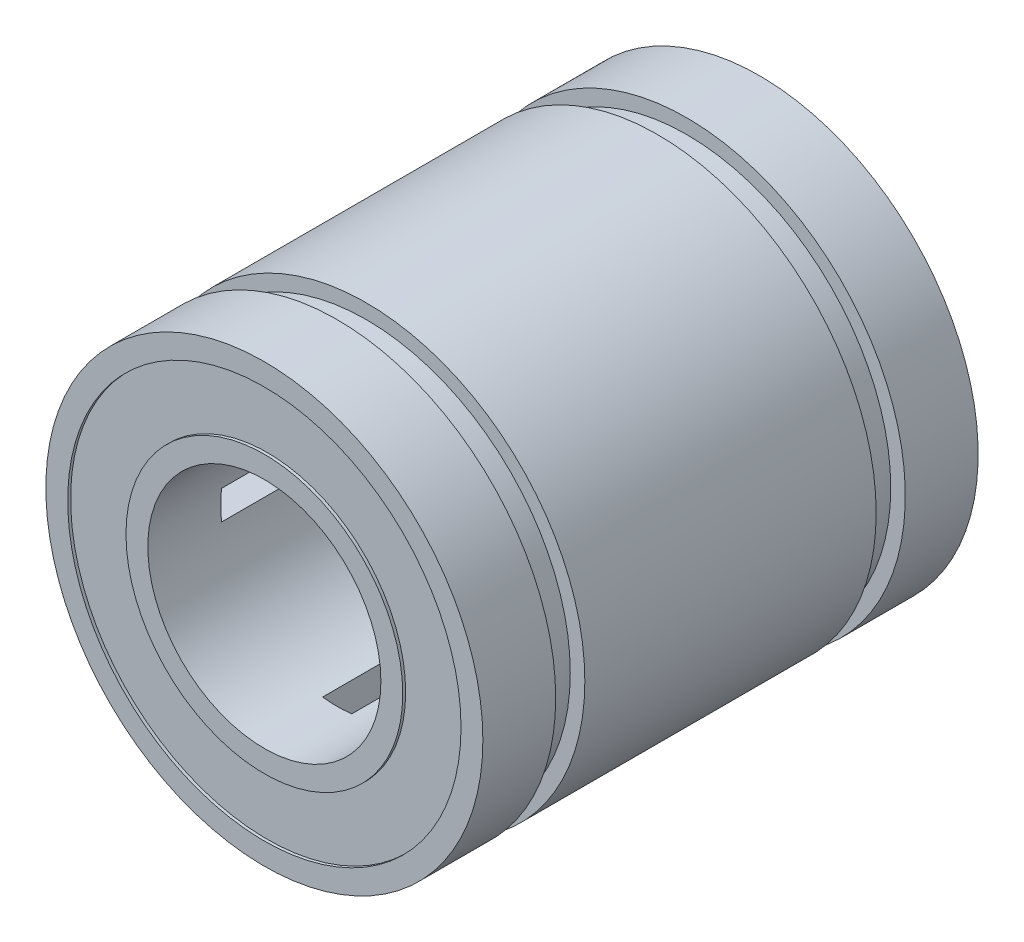
SolidWorks part; units mm, degrees
ref_plane "Front Plane" through (0, 0, 0) normal (0, 0, 1) x (1, 0, 0)
ref_plane "Top Plane" through (0, 0, 0) normal (0, 1, 0) x (1, 0, 0)
ref_plane "Right Plane" through (0, 0, 0) normal (1, 0, 0) x (0, 0, -1)
sketch "Sketch1" plane through (0, 0, 0) normal (0, 0, 1) x (1, 0, 0)
  circle A0 centre (0, 0) radius 7.5
  circle A1 centre (0, 0) radius 4
  dimension "D1" = 15
  dimension "D2" = 8
extrude "Boss-Extrude1" add sketch "Sketch1" along normal blind 10
sketch "Sketch2" plane through (0, 0, 10) normal (0, 0, 1) x (1, 0, 0)
  circle A0 centre (0, 0) radius 7
  dimension "D1" = 14
extrude "Boss-Extrude2" add sketch "Sketch2" along normal blind 1
sketch "Sketch3" plane through (0, 0, 0) normal (0, 0, -1) x (-1, 0, 0)
  circle A0 centre (0, 0) radius 7
  dimension "D1" = 14
extrude "Boss-Extrude3" add sketch "Sketch3" along normal blind 1
sketch "Sketch5" plane through (0, 0, -1) normal (0, 0, -1) x (-1, 0, 0)
  circle A0 centre (0, 0) radius 7.5
  dimension "D1" = 15
extrude "Boss-Extrude4" add sketch "Sketch5" along normal blind 2.5
sketch "Sketch10" plane through (0, 0, 11) normal (0, 0, 1) x (1, 0, 0)
  line L1 (-0.5, 6) -> (0.5, 6)
  line L2 (-0.5, 6) -> (-0.5, -6)
  line L3 (-0.5, -6) -> (0.5, -6)
  line L4 (0.5, 6) -> (0.5, -6)
  line L5 (-0.5, 6) -> (0.5, -6) construction
  line L6 (-0.5, -6) -> (0.5, 6) construction
  point P0 (0, 0)
  dimension "D1" = 12
  dimension "D2" = 1
extrude "Cut-Extrude4" cut sketch "Sketch10" against normal blind 10
sketch "Sketch11" plane through (0, 0, 11) normal (0, 0, 1) x (1, 0, 0)
  line L1 (-6, 0.5) -> (6, 0.5)
  line L2 (-6, 0.5) -> (-6, -0.5)
  line L3 (-6, -0.5) -> (6, -0.5)
  line L4 (6, 0.5) -> (6, -0.5)
  line L5 (-6, 0.5) -> (6, -0.5) construction
  line L6 (-6, -0.5) -> (6, 0.5) construction
  point P0 (0, 0)
  dimension "D1" = 12
  dimension "D2" = 1
extrude "Cut-Extrude5" cut sketch "Sketch11" against normal blind 10
sketch "Sketch6" plane through (0, 0, 11) normal (0, 0, 1) x (1, 0, 0)
  circle A0 centre (0, 0) radius 7.5
  dimension "D1" = 15
extrude "Boss-Extrude6" add sketch "Sketch6" along normal blind 2.5
sketch "Sketch7" plane through (0, 0, 13.5) normal (0, 0, 1) x (1, 0, 0)
  circle A0 centre (0, 0) radius 4
  dimension "D1" = 8
extrude "Cut-Extrude1" cut sketch "Sketch7" against normal blind 17
sketch "Sketch8" plane through (0, 0, 13.5) normal (0, 0, 1) x (1, 0, 0)
  circle A0 centre (0, 0) radius 4.75
  circle A1 centre (0, 0) radius 6.75
  dimension "D1" = 9.5
  dimension "D2" = 2
extrude "Cut-Extrude2" cut sketch "Sketch8" against normal blind 0.1
sketch "Sketch9" plane through (0, 0, -3.5) normal (0, 0, -1) x (-1, 0, 0)
  circle A0 centre (0, 0) radius 4.75
  circle A1 centre (0, 0) radius 6.75
  dimension "D1" = 9.5
  dimension "D2" = 2
extrude "Cut-Extrude3" cut sketch "Sketch9" against normal blind 0.1
